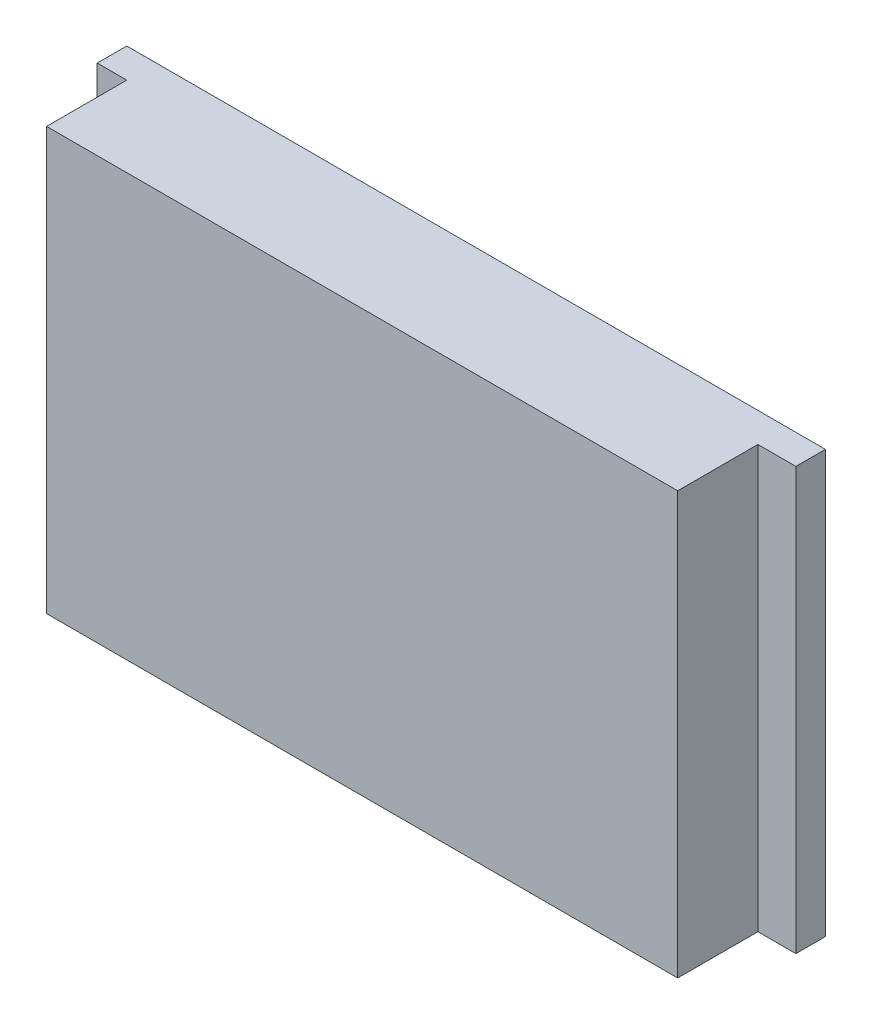
SolidWorks part; units mm, degrees
ref_plane "Plan de face" through (0, 0, 0) normal (0, 0, 1) x (1, 0, 0)
ref_plane "Plan de dessus" through (0, 0, 0) normal (0, 1, 0) x (1, 0, 0)
ref_plane "Plan de droite" through (0, 0, 0) normal (1, 0, 0) x (0, 0, -1)
sketch "Esquisse1" plane through (0, 0, 0) normal (0, 0, 1) x (1, 0, 0)
  line L1 (-82.78, 50) -> (82.78, 50)
  line L2 (-82.78, 50) -> (-82.78, -50)
  line L3 (-82.78, -50) -> (82.78, -50)
  line L4 (82.78, 50) -> (82.78, -50)
  point P4 (0, -50)
  point P5 (82.78, 0)
  dimension "D1" = 100
  dimension "D2" = 165.56
extrude "Boss.-Extru.1" add sketch "Esquisse1" along normal blind 7
sketch "Esquisse2" plane through (0, 0, 7) normal (0, 0, 1) x (1, 0, 0)
  line L0 (82.78, 50) -> (-82.78, 50) construction
  line L1 (-75.78, 50) -> (73.78, 50)
  line L2 (-75.78, 50) -> (-75.78, -50)
  line L3 (-75.78, -50) -> (73.78, -50)
  line L4 (73.78, 50) -> (73.78, -50)
  line L5 (-82.78, -50) -> (82.78, -50) construction
  line L6 (-82.78, 50) -> (-82.78, -50) construction
  line L7 (82.78, -50) -> (82.78, 50) construction
  dimension "D1" = 7
  dimension "D2" = 9
extrude "Boss.-Extru.2" add sketch "Esquisse2" along normal blind 19
sketch "Esquisse3" plane through (0, 0, 26) normal (0, 0, 1) x (1, 0, 0)
  line L0 (-75.78, -50) -> (73.78, -50) construction
  line L1 (-52.78, -15) -> (-18.78, -15)
  line L2 (-52.78, -15) -> (-52.78, -27)
  line L3 (-52.78, -27) -> (-18.78, -27)
  line L4 (-18.78, -15) -> (-18.78, -27)
  line L5 (-52.78, 27) -> (-18.78, 27)
  line L6 (-52.78, 27) -> (-52.78, 15)
  line L7 (-52.78, 15) -> (-18.78, 15)
  line L8 (-18.78, 27) -> (-18.78, 15)
  line L9 (-82.78, 50) -> (-82.78, -50) construction
  line L10 (73.78, 50) -> (-75.78, 50) construction
  line L11 (0, -14.3) -> (0, 14.3) construction
  line L12 (52.78, -27) -> (18.78, -27)
  line L13 (18.78, -15) -> (18.78, -27)
  line L14 (52.78, -15) -> (18.78, -15)
  line L15 (52.78, -15) -> (52.78, -27)
  line L16 (52.78, 15) -> (18.78, 15)
  line L17 (18.78, 27) -> (18.78, 15)
  line L18 (52.78, 27) -> (18.78, 27)
  line L19 (52.78, 27) -> (52.78, 15)
  dimension "D1" = 23
  dimension "D2" = 30
  dimension "D3" = 12
  dimension "D4" = 34
  dimension "D5" = 30
  dimension "D6" = 23
